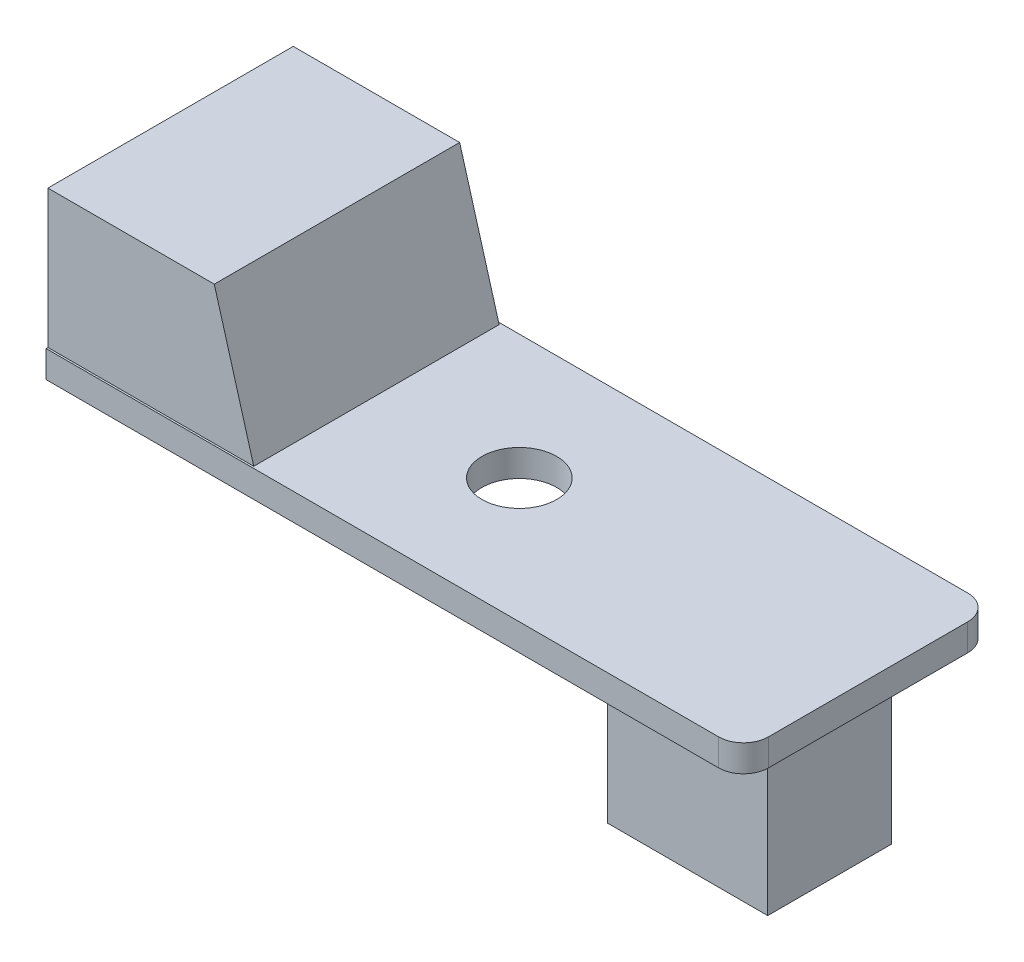
SolidWorks part; units mm, degrees
ref_plane "Front Plane" through (0, 0, 0) normal (0, 0, 1) x (1, 0, 0)
ref_plane "Top Plane" through (0, 0, 0) normal (0, 1, 0) x (1, 0, 0)
ref_plane "Right Plane" through (0, 0, 0) normal (1, 0, 0) x (0, 0, -1)
sketch "Sketch1" plane through (0, 0, 0) normal (0, 1, 0) x (1, 0, 0)
  line L4 (0, 0) -> (27, 0)
  line L5 (28, 1) -> (28, 9)
  line L6 (27, 10) -> (0, 10)
  line L7 (0, 10) -> (0, 0)
  arc A0 (27, 0) -> (28, 1) centre (27, 1) ccw
  arc A1 (28, 9) -> (27, 10) centre (27, 9) ccw
  circle A2 centre (14, 5) radius 1.5
  dimension "D1" = 28
  dimension "D4" = 1
  dimension "D3" = 1
  dimension "D7" = 3
  dimension "D2" = 10
  dimension "D5" = 5
  dimension "D6" = 14
extrude "Boss-Extrude1" add sketch "Sketch1" along normal blind 1.08
sketch "Sketch2" plane through (0, 1.08, 0) normal (0, 1, 0) x (1, 0, 0)
  line L0 (0, 9.925) -> (6.68, 9.925)
  line L1 (0, 10) -> (0, 0) construction
  line L2 (6.68, 9.925) -> (6.68, 0.075)
  line L3 (6.68, 0.075) -> (0, 0.075)
  line L4 (0, 0.075) -> (0, 9.925)
  line L5 (27, 10) -> (0, 10) construction
  point P5 (0, 5)
  dimension "D1" = 5
  dimension "D2" = 9.85
  dimension "D3" = 6.68
extrude "Boss-Extrude2" add sketch "Sketch2" along normal blind 5.54
sketch "Sketch3" plane through (0, 0, -0.075) normal (0, 0, 1) x (1, 0, 0)
  line L0 (0, 1.08) -> (8.2646, 1.08)
  line L1 (0, 1.08) -> (27, 1.08) construction
  line L2 (8.2646, 1.08) -> (6.68, 6.62)
  line L3 (6.68, 6.62) -> (0, 6.62)
  line L4 (0, 6.62) -> (0, 1.08)
extrude "Boss-Extrude3" add sketch "Sketch3" against normal blind 9.85
sketch "Sketch4" plane through (0, 0, 0) normal (0, -1, 0) x (1, 0, 0)
  line L0 (20.02, -2.52) -> (20.02, -7.48)
  line L1 (20.02, -7.48) -> (26.45, -7.48)
  line L2 (26.45, -7.48) -> (26.45, -2.52)
  line L3 (26.45, -2.52) -> (20.02, -2.52)
  line L4 (0, 0) -> (27, 0) construction
  line L5 (28, -1) -> (28, -9) construction
  point P2 (26.45, -5)
  dimension "D1" = 5
  dimension "D2" = 7.98
  dimension "D3" = 6.43
  dimension "D4" = 4.96
extrude "Boss-Extrude4" add sketch "Sketch4" along normal blind 6.67
